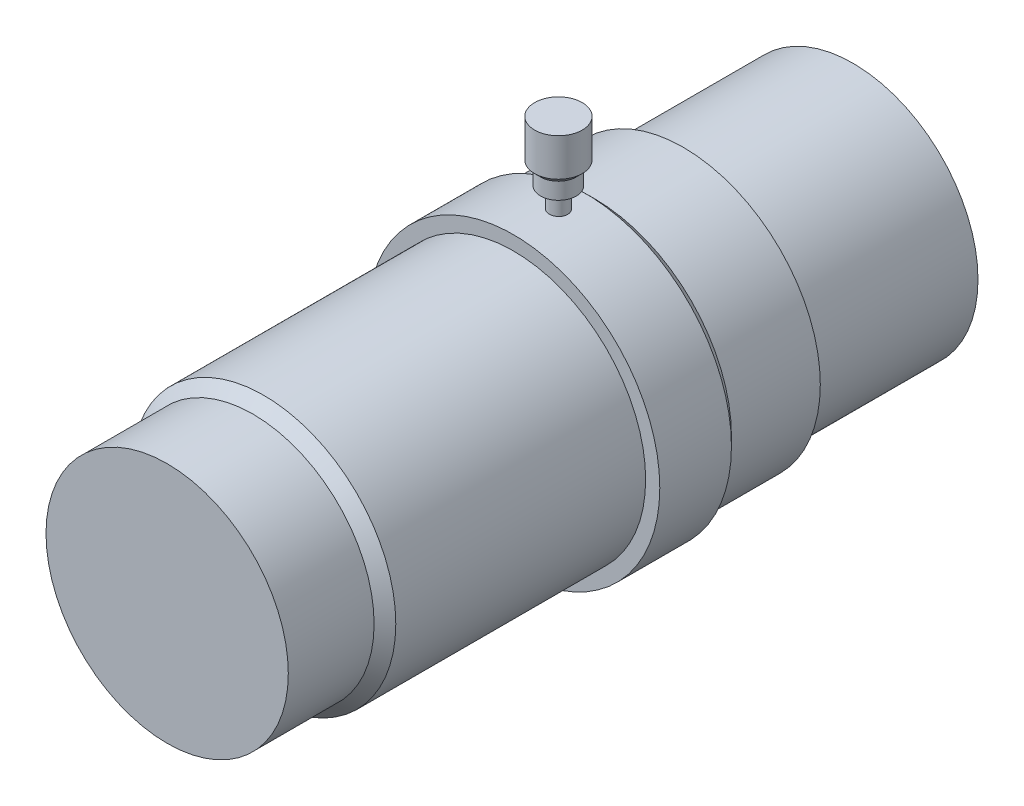
SolidWorks part; units mm, degrees
ref_plane "Front Plane" through (0, 0, 0) normal (0, 0, 1) x (1, 0, 0)
ref_plane "Top Plane" through (0, 0, 0) normal (0, 1, 0) x (1, 0, 0)
ref_plane "Right Plane" through (0, 0, 0) normal (1, 0, 0) x (0, 0, -1)
sketch "Sketch1" plane through (0, 0, 0) normal (1, 0, 0) x (0, 0, -1)
  line L0 (0, 0) -> (-145.5, 0)
  line L1 (-145.5, 0) -> (-145.5, 25.7)
  line L2 (-145.5, 25.7) -> (-127.3, 25.7)
  line L3 (-127.3, 25.7) -> (-125, 28)
  line L4 (-125, 28) -> (-72, 28)
  line L5 (-72, 28) -> (-72, 31)
  line L6 (-72, 31) -> (-56.8, 31)
  line L7 (-56.8, 31) -> (-54.85, 29.05)
  line L8 (-54.85, 29.05) -> (-36, 29.05)
  line L9 (-36, 29.05) -> (-36, 26.5)
  line L10 (-36, 26.5) -> (0, 26.5)
  line L11 (0, 26.5) -> (0, 0)
  line L12 (0, 0) -> (62.5249, 0) construction
  point P3 (-54.2302, 29.05)
  dimension "D1" = 53
  dimension "D2" = 58.1
  dimension "D3" = 62
  dimension "D4" = 56
  dimension "D5" = 51.4
  dimension "D6" = 36
  dimension "D7" = 56.8
  dimension "D8" = 45
  dimension "D9" = 72
  dimension "D10" = 125
  dimension "D11" = 45
  dimension "D12" = 145.5
revolve "Revolve1" add sketch "Sketch1" angle 360 about L12
sketch "Sketch2" plane through (0, 0, 0) normal (1, 0, 0) x (0, 0, -1)
  line L0 (-62.5, 31) -> (-62.5, 48)
  line L2 (-62.5, 48) -> (-57.45, 48)
  line L3 (-57.45, 48) -> (-57.45, 40)
  line L4 (-57.45, 40) -> (-58.7, 38.75)
  line L5 (-58.7, 38.75) -> (-58.7, 35.25)
  line L6 (-58.7, 35.25) -> (-60.55, 35.25)
  line L7 (-60.55, 35.25) -> (-60.55, 29)
  line L8 (-60.55, 29) -> (-62.5, 29)
  line L9 (-62.5, 29) -> (-62.5, 31)
  line L10 (-62.5, 48) -> (-62.5, 54) construction
  line L11 (-56.8, 31) -> (-72, 31) construction
  point P4 (0, 0)
  dimension "D1" = 10.1
  dimension "D2" = 17
  dimension "D3" = 8
  dimension "D4" = 12.75
  dimension "D5" = 3.9
  dimension "D6" = 7.6
  dimension "D7" = 2
  dimension "D8" = 45
  dimension "D9" = 6
  dimension "D10" = 62.5
revolve "Revolve2" add sketch "Sketch2" angle 360 about L10
